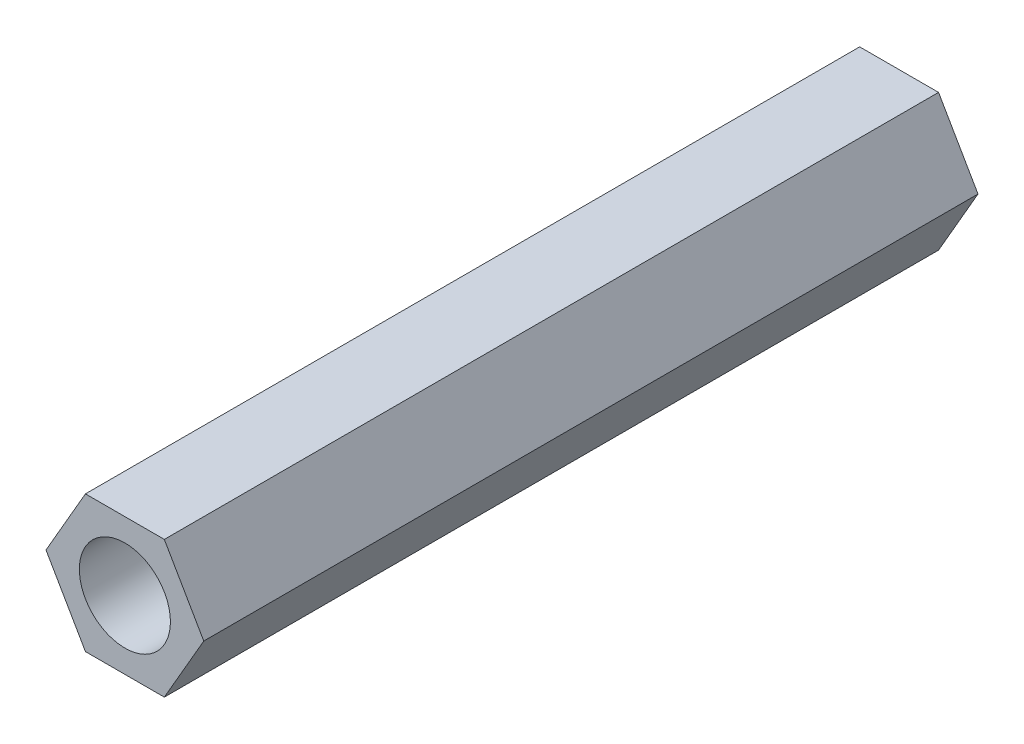
SolidWorks part; units mm, degrees
ref_plane "前视基准面" through (0, 0, 0) normal (0, 0, 1) x (1, 0, 0)
ref_plane "上视基准面" through (0, 0, 0) normal (0, 1, 0) x (1, 0, 0)
ref_plane "右视基准面" through (0, 0, 0) normal (1, 0, 0) x (0, 0, -1)
sketch "草图1" plane through (0, 0, 0) normal (0, 0, 1) x (1, 0, 0)
  line L1 (1.7321, 0) -> (0.866, 1.5)
  line L2 (0.866, 1.5) -> (-0.866, 1.5)
  line L3 (-0.866, 1.5) -> (-1.7321, 0)
  line L4 (-1.7321, 0) -> (-0.866, -1.5)
  line L5 (-0.866, -1.5) -> (0.866, -1.5)
  line L6 (0.866, -1.5) -> (1.7321, 0)
  circle A0 centre (0, 0) radius 1
  circle A1 centre (0, 0) radius 1.5 construction
  dimension "D1" = 2
  dimension "D2" = 3
extrude "凸台-拉伸1" add sketch "草图1" along normal blind 17
